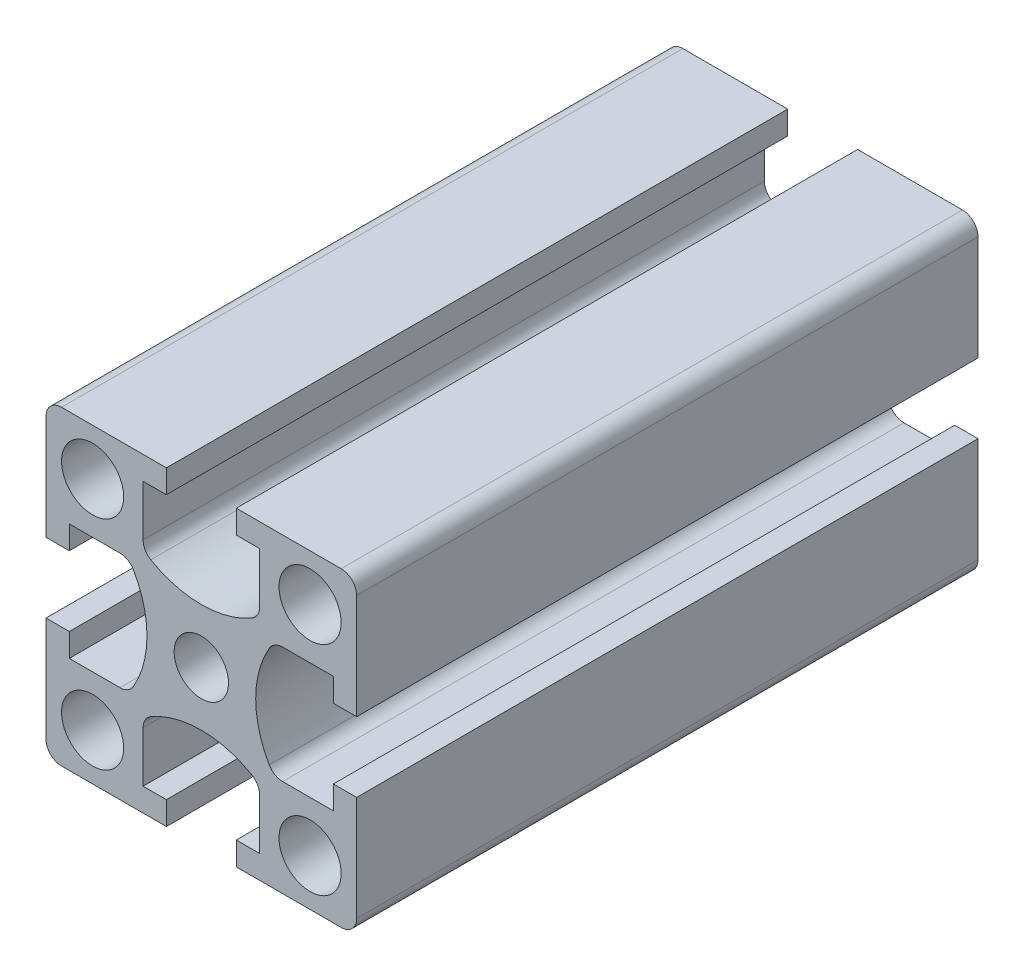
SolidWorks part; units mm, degrees
ref_plane "Front Plane" through (0, 0, 0) normal (0, 0, 1) x (1, 0, 0)
ref_plane "Top Plane" through (0, 0, 0) normal (0, 1, 0) x (1, 0, 0)
ref_plane "Right Plane" through (0, 0, 0) normal (1, 0, 0) x (0, 0, -1)
sketch "Sketch1" plane through (0, 0, 0) normal (0, 0, 1) x (1, 0, 0)
  line L64 (-25, 22.5) -> (-25, 5.625)
  line L65 (-25, 5.625) -> (-21.25, 5.625)
  line L66 (-21.25, 5.625) -> (-21.25, 9.375)
  line L67 (-21.25, 9.375) -> (-13.0922, 9.375)
  line L68 (-13.0922, -9.375) -> (-21.25, -9.375)
  line L69 (-21.25, -9.375) -> (-21.25, -5.625)
  line L70 (-21.25, -5.625) -> (-25, -5.625)
  line L71 (-25, -5.625) -> (-25, -22.5)
  line L72 (-22.5, -25) -> (-5.625, -25)
  line L73 (-5.625, -25) -> (-5.625, -21.25)
  line L74 (-5.625, -21.25) -> (-9.375, -21.25)
  line L75 (-9.375, -21.25) -> (-9.375, -13.0922)
  line L76 (9.375, -13.0922) -> (9.375, -21.25)
  line L77 (9.375, -21.25) -> (5.625, -21.25)
  line L78 (5.625, -21.25) -> (5.625, -25)
  line L79 (5.625, -25) -> (22.5, -25)
  line L80 (25, -22.5) -> (25, -5.625)
  line L81 (25, -5.625) -> (21.25, -5.625)
  line L82 (21.25, -5.625) -> (21.25, -9.375)
  line L83 (21.25, -9.375) -> (13.0922, -9.375)
  line L84 (13.0922, 9.375) -> (21.25, 9.375)
  line L85 (21.25, 9.375) -> (21.25, 5.625)
  line L86 (21.25, 5.625) -> (25, 5.625)
  line L87 (25, 5.625) -> (25, 22.5)
  line L88 (22.5, 25) -> (5.625, 25)
  line L89 (5.625, 25) -> (5.625, 21.25)
  line L90 (5.625, 21.25) -> (9.375, 21.25)
  line L91 (9.375, 21.25) -> (9.375, 13.0922)
  line L92 (-9.375, 13.0922) -> (-9.375, 21.25)
  line L93 (-9.375, 21.25) -> (-5.625, 21.25)
  line L94 (-5.625, 21.25) -> (-5.625, 25)
  line L95 (-5.625, 25) -> (-22.5, 25)
  circle A5 centre (-17.5, -17.5) radius 5
  circle A6 centre (17.5, -17.5) radius 5
  circle A7 centre (17.5, 17.5) radius 5
  circle A8 centre (0, 0) radius 4.375
  circle A9 centre (-17.5, 17.5) radius 5
  arc A32 (-22.5, 25) -> (-25, 22.5) centre (-22.5, 22.5) ccw
  arc A33 (-10.9271, 8.125) -> (-13.0922, 9.375) centre (-13.0922, 6.875) ccw
  arc A34 (-10.9271, -8.125) -> (-10.9271, 8.125) centre (-25, 0) ccw
  arc A35 (-13.0922, -9.375) -> (-10.9271, -8.125) centre (-13.0922, -6.875) ccw
  arc A36 (-25, -22.5) -> (-22.5, -25) centre (-22.5, -22.5) ccw
  arc A37 (-8.125, -10.9271) -> (-9.375, -13.0922) centre (-6.875, -13.0922) ccw
  arc A38 (8.125, -10.9271) -> (-8.125, -10.9271) centre (0, -25) ccw
  arc A39 (9.375, -13.0922) -> (8.125, -10.9271) centre (6.875, -13.0922) ccw
  arc A40 (22.5, -25) -> (25, -22.5) centre (22.5, -22.5) ccw
  arc A41 (10.9271, -8.125) -> (13.0922, -9.375) centre (13.0922, -6.875) ccw
  arc A42 (10.9271, 8.125) -> (10.9271, -8.125) centre (25, 0) ccw
  arc A43 (13.0922, 9.375) -> (10.9271, 8.125) centre (13.0922, 6.875) ccw
  arc A44 (25, 22.5) -> (22.5, 25) centre (22.5, 22.5) ccw
  arc A45 (8.125, 10.9271) -> (9.375, 13.0922) centre (6.875, 13.0922) ccw
  arc A46 (-8.125, 10.9271) -> (8.125, 10.9271) centre (0, 25) ccw
  arc A47 (-9.375, 13.0922) -> (-8.125, 10.9271) centre (-6.875, 13.0922) ccw
  dimension "D3" = 10
  dimension "D4" = 8.75
  dimension "D8" = 16.25
  dimension "D9" = 2.5
  dimension "D15" = 16.25
  dimension "D1" = 50
  dimension "D2" = 50
  dimension "D5" = 19.375
  dimension "D6" = 19.375
  dimension "D7" = 3.75
  dimension "D10" = 8.1578
  dimension "D11" = 3.75
  dimension "D12" = 8.1578
  dimension "D13" = 3.75
  dimension "D14" = 3.75
extrude "Boss-Extrude1" add sketch "Sketch1" along normal blind 100
